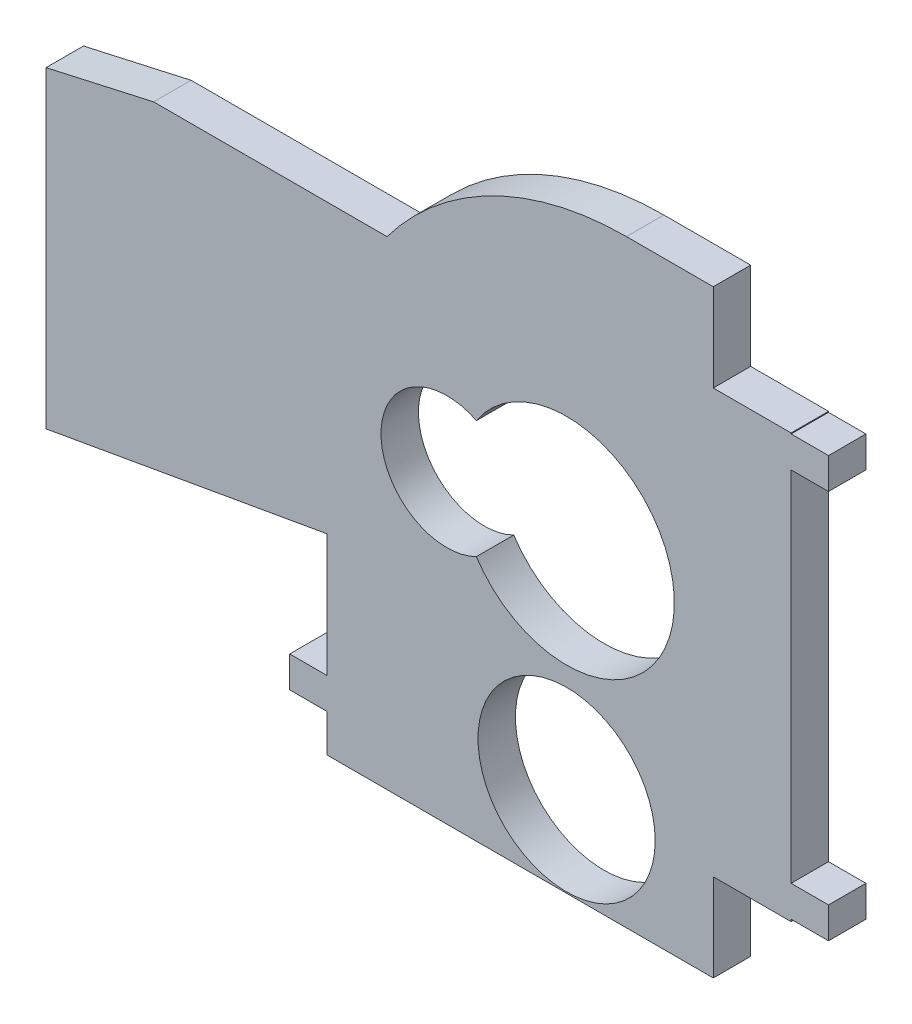
SolidWorks part; units mm, degrees
material "Balsa"
ref_plane "Front Plane" through (0, 0, 0) normal (0, 0, 1) x (1, 0, 0)
ref_plane "Top Plane" through (0, 0, 0) normal (0, 1, 0) x (1, 0, 0)
ref_plane "Right Plane" through (0, 0, 0) normal (1, 0, 0) x (0, 0, -1)
sketch "Sketch1" plane through (0, 0, 0) normal (0, 0, 1) x (1, 0, 0)
  line L0 (0, -1000.1535) -> (0, 48999.8465) construction
  line L1 (0, 9.144) -> (-5.08, 9.144) construction
  line L2 (-1000, 0) -> (49000, 0) construction
  line L3 (9.525, 16.51) -> (11.1125, 16.51)
  line L4 (2.54, 21.59) -> (9.525, 21.59)
  line L5 (-10.16, 8.89) -> (-10.16, -3.81)
  line L6 (-10.16, -3.81) -> (9.525, -3.81)
  line L7 (9.525, 21.59) -> (9.525, -3.81)
  line L8 (-11.7475, -2.2098) -> (-10.16, -2.2098)
  line L9 (-11.7475, -2.2098) -> (-11.7475, -0.889)
  line L10 (-11.7475, -0.889) -> (-10.16, -0.889)
  line L11 (-10.16, -2.2098) -> (-10.16, -0.889)
  line L12 (9.525, 0) -> (11.1125, 0)
  line L13 (9.525, 0) -> (9.525, 1.3208)
  line L14 (9.525, 1.3208) -> (11.1125, 1.3208)
  line L15 (11.1125, 0) -> (11.1125, 1.3208)
  line L16 (9.525, 16.51) -> (9.525, 17.8308)
  line L17 (9.525, 17.8308) -> (11.1125, 17.8308)
  line L18 (11.1125, 16.51) -> (11.1125, 17.8308)
  line L19 (-7.62, 16.51) -> (-22.0849, 16.51)
  line L21 (-22.0849, 2.212) -> (-10.16, 4.318)
  line L22 (9.525, 8.89) -> (-35.5862, 8.89) construction
  line L27 (-22.0849, 13.081) -> (-22.0849, 4.699)
  line L29 (-22.0849, 15.487) -> (-17.5195, 16.51)
  line L30 (-22.0849, 13.081) -> (-22.0849, 15.487)
  line L31 (9.525, 12.7762) -> (9.525, 4.9022)
  line L32 (-22.0849, 4.699) -> (-22.0849, 2.212)
  line L33 (-22.0849, 15.487) -> (-22.0849, 16.51)
  circle A0 centre (0, 0) radius 3.7592
  arc A1 (-3.829, 6.6457) -> (-3.829, 11.6423) centre (0, 9.144) ccw
  arc A2 (-3.829, 11.6423) -> (-3.829, 6.6457) centre (-5.08, 9.144) ccw
  arc A3 (2.54, 21.59) -> (-10.16, 8.89) centre (2.54, 8.89) ccw
  point P33 (9.525, 8.89)
  point P35 (-27.4189, 8.89)
  dimension "D1" = 7.5184
  dimension "D4" = 3.81
  dimension "D3" = 9.144
  dimension "D5" = 2.794
  dimension "D9" = 12.7
  dimension "D10" = 1.5875
  dimension "D2" = 25.4
  dimension "D6" = 9.525
  dimension "D7" = 5.08
  dimension "D8" = 19.685
  dimension "D11" = 9.144
  dimension "D12" = 1.3208
  dimension "D13" = 1.3208
  dimension "D14" = 1.5875
  dimension "D15" = 2
  dimension "D16" = 8.128
  dimension "D17" = 5.207
  dimension "D19" = 8.382
  dimension "D21" = 14.4649
  dimension "D22" = 5.08
extrude "Boss-Extrude1" add sketch "Sketch1" along normal blind 1.5875
sketch "Sketch2" plane through (0, 0, 1.5875) normal (0, 0, 1) x (1, 0, 0)
  line L1 (6.223, -3.8481) -> (9.525, -3.8481)
  line L2 (6.223, -3.8481) -> (6.223, -0.0889)
  line L3 (6.223, -0.0889) -> (9.525, -0.0889)
  line L4 (9.525, -3.8481) -> (9.525, -0.0889)
  line L5 (9.525, -0.9144) -> (9.525, -3.0226)
  line L7 (9.525, 20.8026) -> (9.525, 18.6944)
  line L9 (6.223, 17.8689) -> (9.525, 17.8689)
  line L10 (6.223, 17.8689) -> (6.223, 21.6281)
  line L11 (6.223, 21.6281) -> (9.525, 21.6281)
  line L12 (9.525, 17.8689) -> (9.525, 21.6281)
  point P8 (9.525, -1.9685)
  point P9 (9.525, -1.9685)
  point P10 (9.525, 19.7485)
  point P15 (9.525, 19.7485)
  line M4 (9.525, 21.59) -> (2.54, 21.59)
  line M11 (-10.16, -3.81) -> (9.525, -3.81)
  line M12 (9.525, -3.81) -> (9.525, 0)
  line M20 (9.525, 17.8308) -> (9.525, 21.59)
  dimension "D1" = 3.7592
  dimension "D2" = 3.302
  dimension "D3" = 3.7592
  dimension "D4" = 3.302
extrude "Cut-Extrude1" cut sketch "Sketch2" against normal up to next contours L3 L2 L4 M11 M12 | L10 L9 M20 M4
move or copy body "Body-Move/Copy1" [suppressed] bodies to move or copy 102
